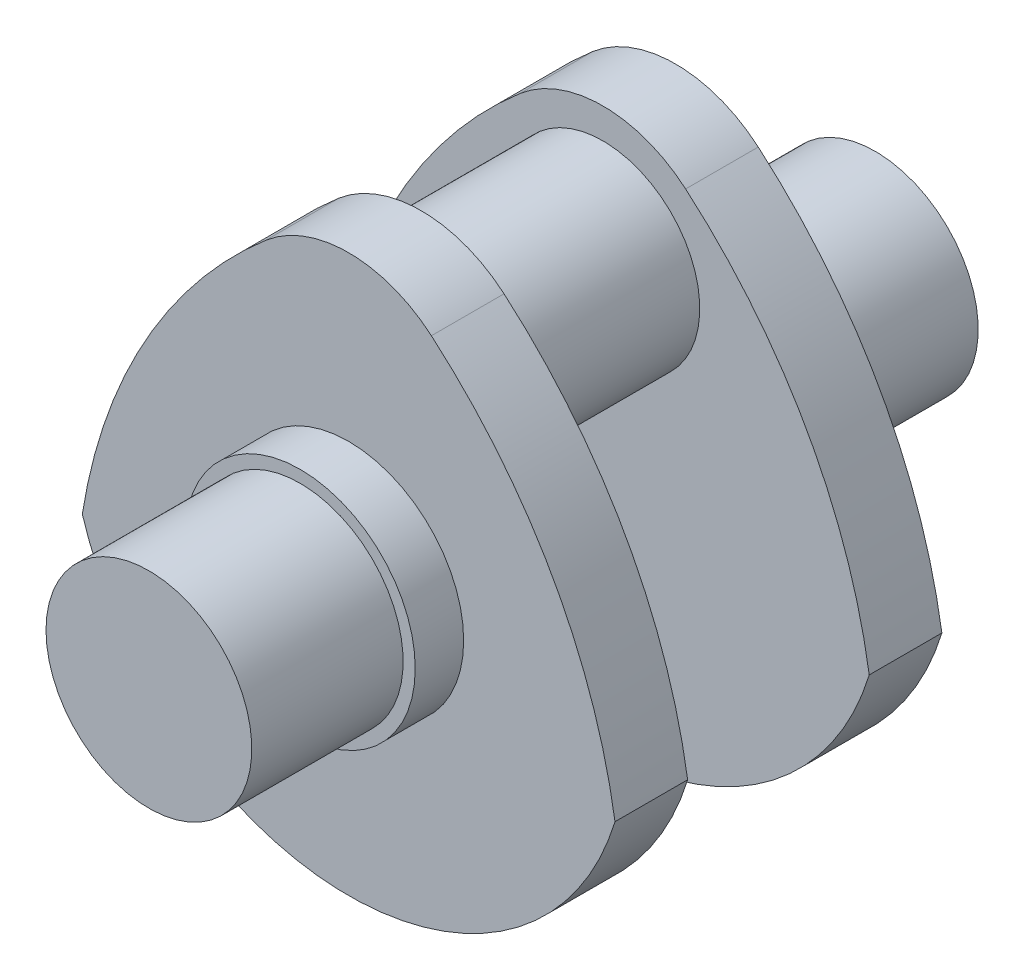
SolidWorks part; units mm, degrees
ref_plane "Front Plane" through (0, 0, 0) normal (0, 0, 1) x (1, 0, 0)
ref_plane "Top Plane" through (0, 0, 0) normal (0, 1, 0) x (1, 0, 0)
ref_plane "Right Plane" through (0, 0, 0) normal (1, 0, 0) x (0, 0, -1)
sketch "Sketch1" plane through (0, 0, 0) normal (0, 0, 1) x (1, 0, 0)
  circle A0 centre (0, 0) radius 431.8
  dimension "D1" = 863.6
extrude "Boss-Extrude1" add sketch "Sketch1" along normal blind 635
sketch "Sketch2" plane through (0, 0, 0) normal (0, 0, 1) x (1, 0, 0)
  circle A0 centre (0, 0) radius 482.6
  dimension "D1" = 965.2
extrude "Boss-Extrude2" add sketch "Sketch2" against normal blind 203.2
sketch "Sketch6" plane through (0, 0, -203.2) normal (0, 0, -1) x (-1, 0, 0)
  arc A0 (-1117.6, -340.7768) -> (1117.6, -340.7768) centre (0, 0) ccw
  arc A1 (347.1696, 1039.9553) -> (-347.1696, 1039.9553) centre (0, 635) ccw
  arc A2 (-347.1696, 1039.9553) -> (-1117.6, -340.7768) centre (1140.7001, -695.5675) ccw
  arc A3 (347.1696, 1039.9553) -> (1117.6, -340.7768) centre (-1140.7001, -695.5675) cw
  dimension "D2" = 1168.4
  dimension "D3" = 1066.8
  dimension "D5" = 2286
  dimension "D6" = 2286
  dimension "D1" = 2235.2
  dimension "D4" = 635
extrude "Boss-Extrude3" add sketch "Sketch6" along normal blind 304.8
sketch "Sketch7" plane through (0, 0, -508) normal (0, 0, -1) x (-1, 0, 0)
  circle A0 centre (0, 635) radius 406.4
  dimension "D1" = 812.8
  dimension "D2" = 635
extrude "Boss-Extrude4" add sketch "Sketch7" along normal blind 381
mirror "Mirror1" about plane through (0, 635, -889) normal (0, 0, -1) of bodies 104
